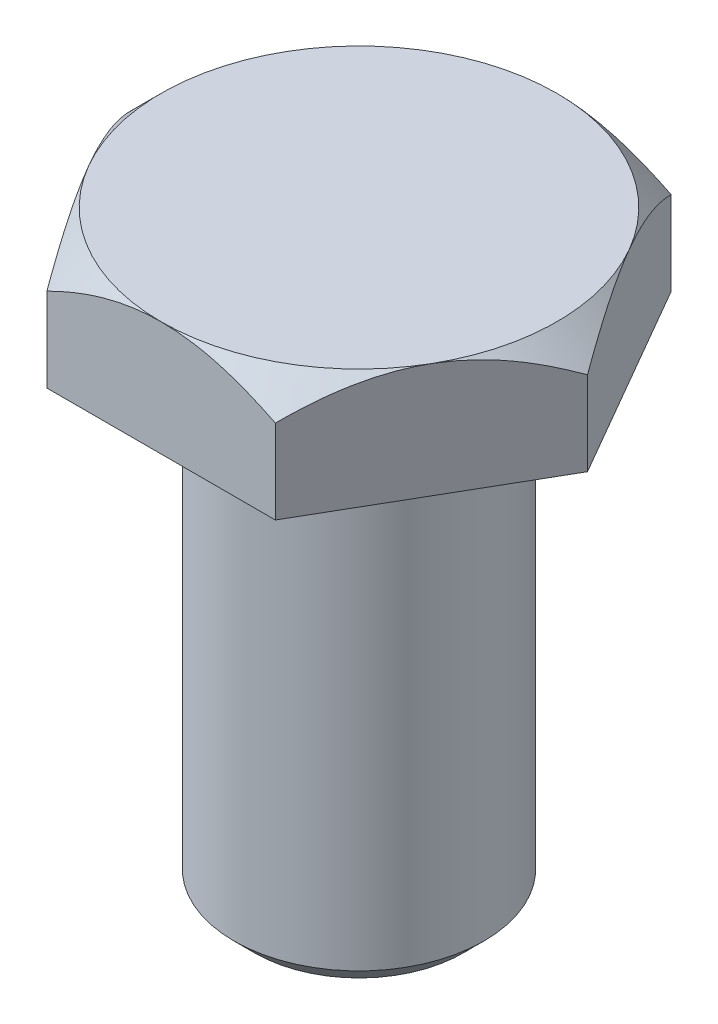
SolidWorks part; units mm, degrees
material "1.5714 (16NiCr4)"
ref_plane "Płaszczyzna przednia" through (0, 0, 0) normal (0, 0, 1) x (1, 0, 0)
ref_plane "Płaszczyzna górna" through (0, 0, 0) normal (0, 1, 0) x (1, 0, 0)
ref_plane "Płaszczyzna prawa" through (0, 0, 0) normal (1, 0, 0) x (0, 0, -1)
sketch "Szkic1" plane through (0, 0, 0) normal (0, 1, 0) x (1, 0, 0)
  circle A0 centre (0, 0) radius 6
  dimension "D1" = 12
extrude "Dodanie-wyciągnięcie1" add sketch "Szkic1" against normal blind 23
sketch "Szkic2" plane through (0, 0, 0) normal (0, 1, 0) x (1, 0, 0)
  line L1 (10.9697, 0) -> (5.4848, 9.5)
  line L2 (5.4848, 9.5) -> (-5.4848, 9.5)
  line L3 (-5.4848, 9.5) -> (-10.9697, 0)
  line L4 (-10.9697, 0) -> (-5.4848, -9.5)
  line L5 (-5.4848, -9.5) -> (5.4848, -9.5)
  line L6 (5.4848, -9.5) -> (10.9697, 0)
  circle A0 centre (0, 0) radius 9.5 construction
  dimension "D1" = 19
extrude "Dodanie-wyciągnięcie2" add sketch "Szkic2" along normal blind 5.5
sketch "Szkic3" plane through (0, 5.5, 0) normal (0, 1, 0) x (1, 0, 0)
  circle A0 centre (0, 0) radius 9.5
sketch "Szkic4" plane through (0, 0, 0) normal (0, 0, 1) x (1, 0, 0)
  line L0 (10.9697, 4.0303) -> (9.5, 5.5)
  line L2 (9.5, 5.5) -> (-9.5, 5.5) construction
  line L3 (9.5, 5.5) -> (10.9697, 5.5)
  line L4 (10.9697, 5.5) -> (10.9697, 4.0303)
sketch "Szkic5" plane through (0, 0, 0) normal (0, 0, 1) x (1, 0, 0)
  line L0 (0, 5.5) -> (0, -23) construction
  line L1 (9.5, 5.5) -> (-9.5, 5.5) construction
  line L2 (-6, -23) -> (6, -23) construction
revolve "Wycięcie-obrót1" cut sketch "Szkic4" angle 360 about L0
chamfer "Sfazowanie1" distance 1 angle 45 1 edges at (0, -23, 6)
